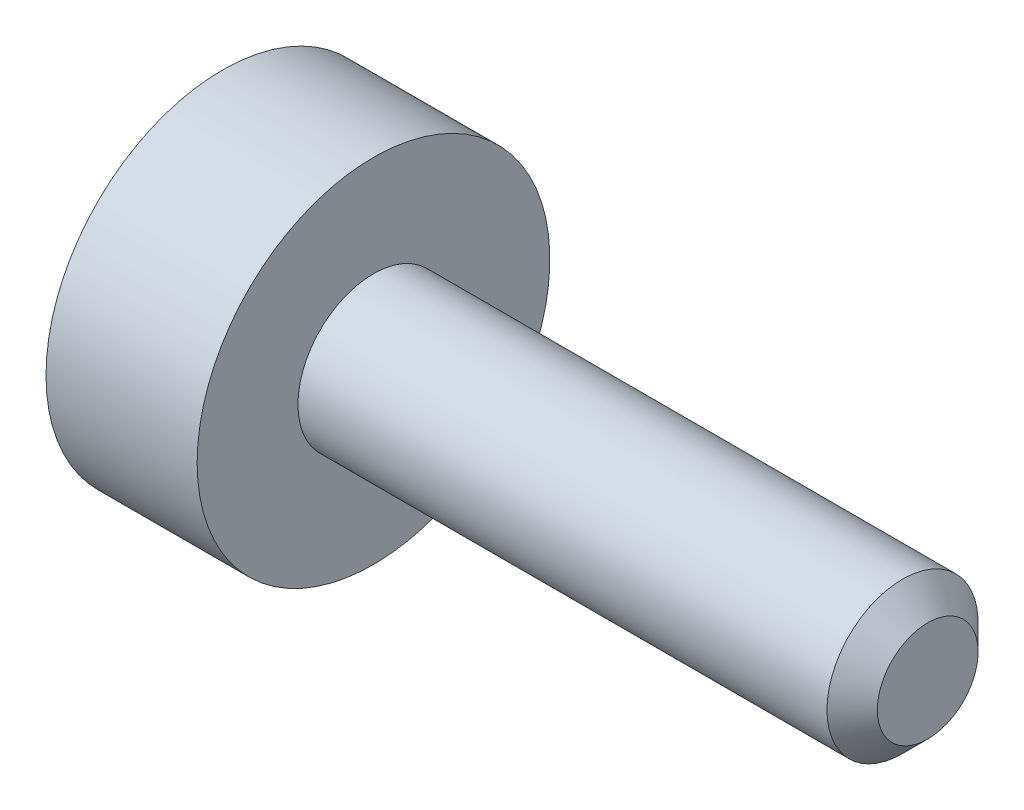
SolidWorks part; units mm, degrees
material "AISI 1020"
ref_plane "Front Plane" through (0, 0, 0) normal (0, 0, 1) x (1, 0, 0)
ref_plane "Top Plane" through (0, 0, 0) normal (0, 1, 0) x (1, 0, 0)
ref_plane "Right Plane" through (0, 0, 0) normal (1, 0, 0) x (0, 0, -1)
sketch "Sketch1" plane through (0, 0, 0) normal (0, 0, 1) x (1, 0, 0)
  line L0 (0, 0) -> (4.55, 0) construction
  line L1 (0, 0) -> (0, 1)
  line L2 (0, 1) -> (-0.5, 1.5)
  line L3 (-0.5, 1.5) -> (-11, 1.5)
  line L4 (-11, 1.5) -> (-11, 3.5)
  line L5 (-11, 3.5) -> (-14, 3.5)
  line L6 (-14, 3.5) -> (-14, 0)
  line L7 (-14, 0) -> (0, 0)
  dimension "D1" = 3
  dimension "D2" = 7
  dimension "D3" = 3
  dimension "D4" = 11
  dimension "D5" = 0.5
  dimension "D6" = 0.5
revolve "Revolve1" add sketch "Sketch1" angle 360 about L0
sketch "Sketch2" plane through (-14, 0, 0) normal (-1, 0, 0) x (0, 0, 1)
  line L1 (0, 1.7321) -> (-1.5, 0.866)
  line L2 (-1.5, 0.866) -> (-1.5, -0.866)
  line L3 (-1.5, -0.866) -> (0, -1.7321)
  line L4 (0, -1.7321) -> (1.5, -0.866)
  line L5 (1.5, -0.866) -> (1.5, 0.866)
  line L6 (1.5, 0.866) -> (0, 1.7321)
  circle A0 centre (0, 0) radius 1.5 construction
  dimension "D1" = 3
extrude "Cut-Extrude1" cut sketch "Sketch2" against normal blind 1.5
